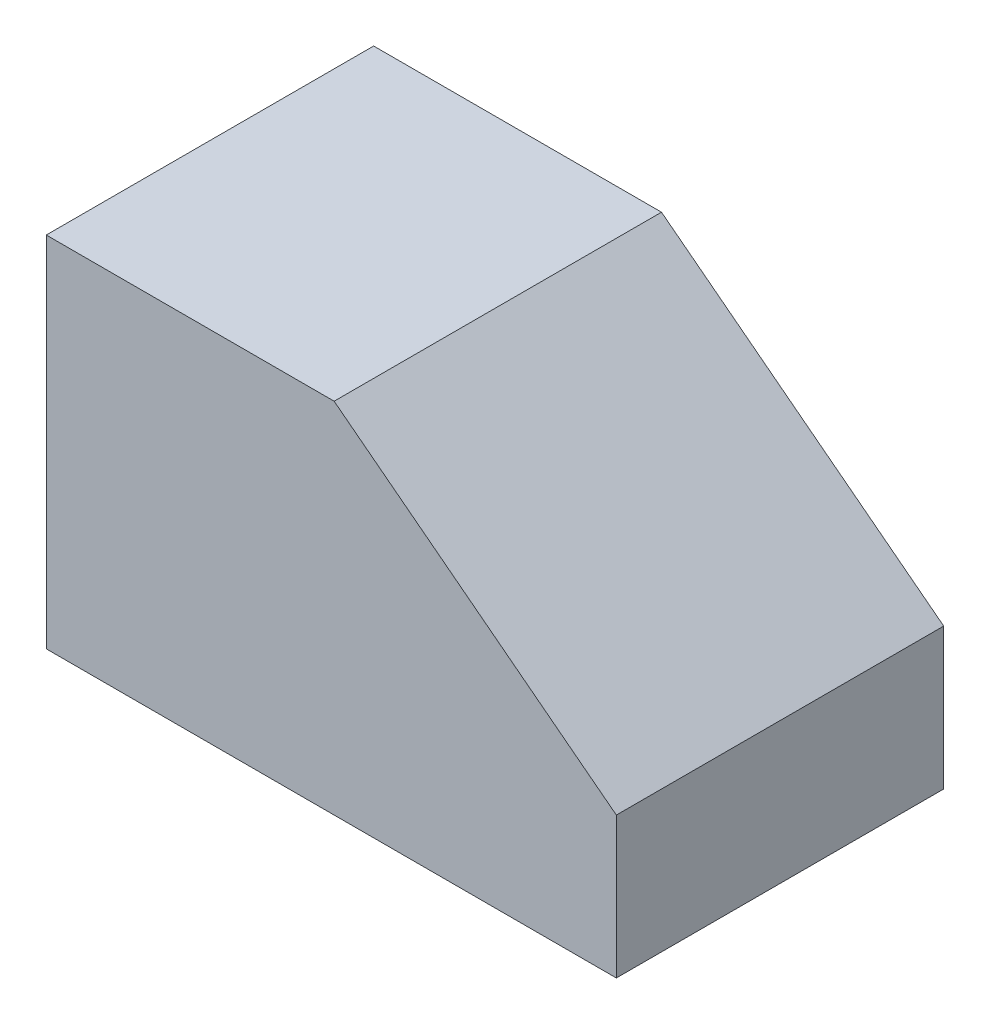
SolidWorks part; units mm, degrees
ref_plane "Front Plane" through (0, 0, 0) normal (0, 0, 1) x (1, 0, 0)
ref_plane "Top Plane" through (0, 0, 0) normal (0, 1, 0) x (1, 0, 0)
ref_plane "Right Plane" through (0, 0, 0) normal (1, 0, 0) x (0, 0, -1)
sketch "Sketch1" plane through (0, 0, 0) normal (0, 0, 1) x (1, 0, 0)
  line L0 (0, 0) -> (101, 0)
  line L1 (101, 0) -> (101, 25)
  line L2 (101, 25) -> (51, 63.5)
  line L3 (51, 63.5) -> (0, 63.5)
  line L4 (0, 63.5) -> (0, 0)
  dimension "D1" = 101
  dimension "D2" = 25
  dimension "D3" = 63.5
  dimension "D4" = 51
extrude "Boss-Extrude1" add sketch "Sketch1" along normal mid plane 58
sketch3d "3DSketch1"
  line L0 (0, 63.5, 29) -> (0, 63.5, 9.95)
  line L1 (0, 63.5, 29) -> (0, 63.5, -29) construction
  line L2 (0, 63.5, 9.95) -> (19.05, 63.5, 29)
  line L3 (51, 63.5, 29) -> (0, 63.5, 29) construction
  line L4 (19.05, 63.5, 29) -> (0, 63.5, 29)
  line L5 (9.525, 63.5, 19.475) -> (0, 38.1, 29) construction
  line L6 (0, 63.5, 29) -> (0, 0, 29) construction
  dimension "D1" = 19.05
  dimension "D2" = 25.4
